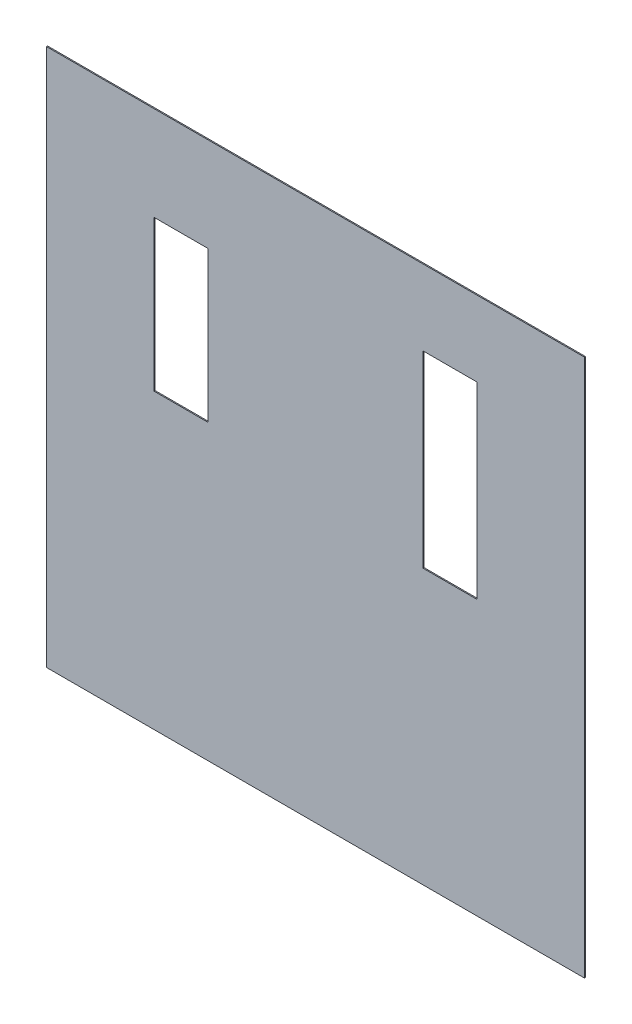
SolidWorks part; units mm, degrees
ref_plane "Front Plane" through (0, 0, 0) normal (0, 0, 1) x (1, 0, 0)
ref_plane "Top Plane" through (0, 0, 0) normal (0, 1, 0) x (1, 0, 0)
ref_plane "Right Plane" through (0, 0, 0) normal (1, 0, 0) x (0, 0, -1)
sketch "Sketch1" plane through (0, 0, 0) normal (0, 0, 1) x (1, 0, 0)
  line L1 (0, 0) -> (25.4, 0)
  line L2 (0, 0) -> (0, 25.4)
  line L3 (0, 25.4) -> (25.4, 25.4)
  line L4 (25.4, 0) -> (25.4, 25.4)
  dimension "D1" = 25.4
  dimension "D2" = 25.4
extrude "Boss-Extrude1" add sketch "Sketch1" along normal blind 0.0508
sketch "Sketch2" plane through (0, 0, 0.0508) normal (0, 0, 1) x (1, 0, 0)
  line L0 (25.4, 25.4) -> (0, 25.4) construction
  line L1 (5.08, 20.955) -> (7.62, 20.955)
  line L2 (5.08, 20.955) -> (5.08, 13.843)
  line L3 (5.08, 13.843) -> (7.62, 13.843)
  line L4 (7.62, 20.955) -> (7.62, 13.843)
  line L5 (17.78, 21.844) -> (20.32, 21.844)
  line L6 (17.78, 21.844) -> (17.78, 12.954)
  line L7 (17.78, 12.954) -> (20.32, 12.954)
  line L8 (20.32, 21.844) -> (20.32, 12.954)
  point P10 (6.35, 20.955)
  point P11 (12.7, 25.4)
  point P12 (6.35, 13.843)
  point P13 (19.05, 12.954)
  dimension "D1" = 2.54
  dimension "D2" = 2.54
  dimension "D3" = 8.89
  dimension "D4" = 7.112
  dimension "D5" = 4.445
  dimension "D6" = 3.556
  dimension "D7" = 6.35
  dimension "D8" = 12.7
extrude "Cut-Extrude1" cut sketch "Sketch2" against normal through all
